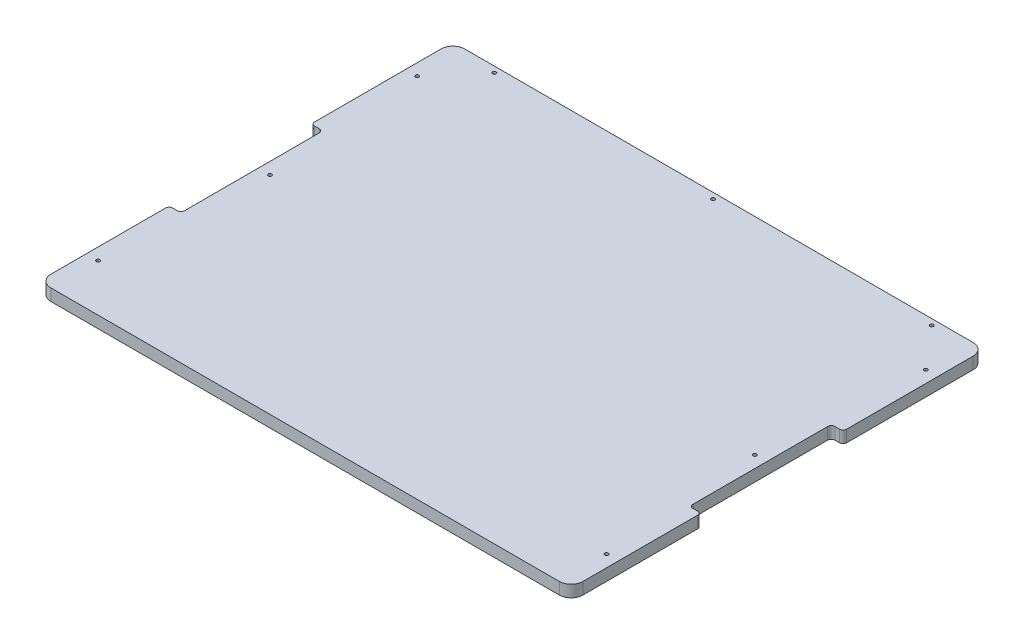
SolidWorks part; units mm, degrees
ref_plane "Front Plane" through (0, 0, 0) normal (0, 0, 1) x (1, 0, 0)
ref_plane "Top Plane" through (0, 0, 0) normal (0, 1, 0) x (1, 0, 0)
ref_plane "Right Plane" through (0, 0, 0) normal (1, 0, 0) x (0, 0, -1)
sketch "Sketch1" plane through (0, 0, 0) normal (0, 1, 0) x (1, 0, 0)
  line L1 (-225, -175) -> (225, -175)
  line L2 (-225, -175) -> (-225, 175)
  line L3 (-225, 175) -> (225, 175)
  line L4 (225, -175) -> (225, 175)
  dimension "D1" = 350
  dimension "D2" = 450
  dimension "D3" = 225
  dimension "D4" = 175
extrude "Boss-Extrude1" add sketch "Sketch1" along normal blind 10
sketch "Sketch2" plane through (0, 10, 0) normal (0, 1, 0) x (1, 0, 0)
  line L0 (225, 175) -> (-225, 175) construction
  line L1 (225, -175) -> (225, 175) construction
  line L2 (-225, 175) -> (-225, -175) construction
  line L3 (-225, -175) -> (225, -175) construction
  circle A0 centre (-215, -135) radius 3
  circle A1 centre (-205, 0.3709) radius 3
  circle A2 centre (-215, 135) radius 3
  circle A3 centre (215, 135) radius 3
  circle A4 centre (205, 0) radius 3
  circle A5 centre (215, -135) radius 3
  circle A6 centre (-185, 170) radius 3
  circle A7 centre (0, 170) radius 3
  circle A8 centre (185, 170) radius 3
  dimension "D1" = 5
  dimension "D2" = 5
  dimension "D3" = 5
  dimension "D4" = 40
  dimension "D5" = 40
  dimension "D6" = 370
  dimension "D7" = 185
  dimension "D8" = 10
  dimension "D9" = 10
  dimension "D10" = 20
  dimension "D11" = 40
  dimension "D12" = 40
  dimension "D13" = 270
  dimension "D14" = 135
  dimension "D15" = 40
  dimension "D16" = 40
  dimension "D17" = 20
  dimension "D18" = 10
  dimension "D19" = 10
  dimension "D20" = 135
extrude "Cut-Extrude1" cut sketch "Sketch2" against normal blind 10
sketch "Sketch3" plane through (0, 10, 0) normal (0, 1, 0) x (1, 0, 0)
  line L0 (-225, 175) -> (-225, -175) construction
  line L1 (-225, 55) -> (-215, 55)
  line L2 (-225, 55) -> (-225, -65)
  line L3 (-225, -65) -> (-215, -65)
  line L4 (-215, 55) -> (-215, -65)
  line L5 (-225, -175) -> (225, -175) construction
  line L10 (225, -175) -> (225, 175) construction
  line L11 (225, -65) -> (215, -65)
  line L12 (225, -65) -> (225, 55)
  line L13 (225, 55) -> (215, 55)
  line L14 (215, -65) -> (215, 55)
  dimension "D1" = 110
  dimension "D2" = 120
  dimension "D3" = 10
  dimension "D4" = 10
  dimension "D5" = 110
  dimension "D6" = 120
extrude "Cut-Extrude2" cut sketch "Sketch3" against normal blind 10
fillet "Fillet1" radius 3 4 edges at (-215, 5, -55) (-215, 5, 65) (215, 5, 65) (215, 5, -55)
fillet "Fillet2" radius 3 4 edges at (225, 5, 65) (225, 5, -55) (-225, 5, 65) (-225, 5, -55)
fillet "Fillet3" radius 10 4 edges at (-225, 5, -175) (-225, 5, 175) (225, 5, 175) (225, 5, -175)
sketch "Sketch5" plane through (0, 10, 0) normal (0, 1, 0) x (1, 0, 0)
  circle A2 centre (-215, 135) radius 3
extrude "Boss-Extrude3" add sketch "Sketch5" against normal blind 10
sketch "Sketch6" plane through (0, 10, 0) normal (0, 1, 0) x (1, 0, 0)
  circle A0 centre (-185, 170) radius 3
  circle A1 centre (0, 170) radius 3
  circle A2 centre (185, 170) radius 3
  circle A3 centre (215, 135) radius 3
  circle A4 centre (205, 0) radius 3
  circle A5 centre (215, -135) radius 3
  circle A6 centre (-215, -135) radius 3
  circle A7 centre (-205, 0.3709) radius 3
extrude "Boss-Extrude4" add sketch "Sketch6" against normal blind 10
sketch "Sketch7" plane through (0, 10, 0) normal (0, 1, 0) x (1, 0, 0)
  line L0 (-225, 165) -> (-225, 58) construction
  line L1 (225, 58) -> (225, 165) construction
  line L2 (215, 175) -> (-215, 175) construction
  line L3 (225, -165) -> (225, -68) construction
  line L4 (-215, -175) -> (215, -175) construction
  line L5 (-225, -68) -> (-225, -165) construction
  circle A2 centre (-185, 170) radius 1.5
  circle A3 centre (-215.1408, 135) radius 1.5
  circle A4 centre (-205, 0.3814) radius 1.5
  circle A5 centre (-215, -135) radius 1.5
  circle A6 centre (215, -135) radius 1.5
  circle A7 centre (205, 0.3709) radius 1.5
  circle A8 centre (215, 135) radius 1.5
  circle A9 centre (0, 170) radius 1.5
  circle A10 centre (185, 170) radius 1.5
  dimension "D1" = 40
  dimension "D2" = 185
  dimension "D3" = 40
  dimension "D4" = 5
  dimension "D5" = 5
  dimension "D6" = 5
  dimension "D7" = 10
  dimension "D8" = 40
  dimension "D9" = 20
  dimension "D10" = 10
  dimension "D11" = 40
  dimension "D12" = 10
  dimension "D13" = 40
  dimension "D14" = 20
  dimension "D15" = 135
  dimension "D16" = 40
extrude "Cut-Extrude3" cut sketch "Sketch7" against normal blind 10
